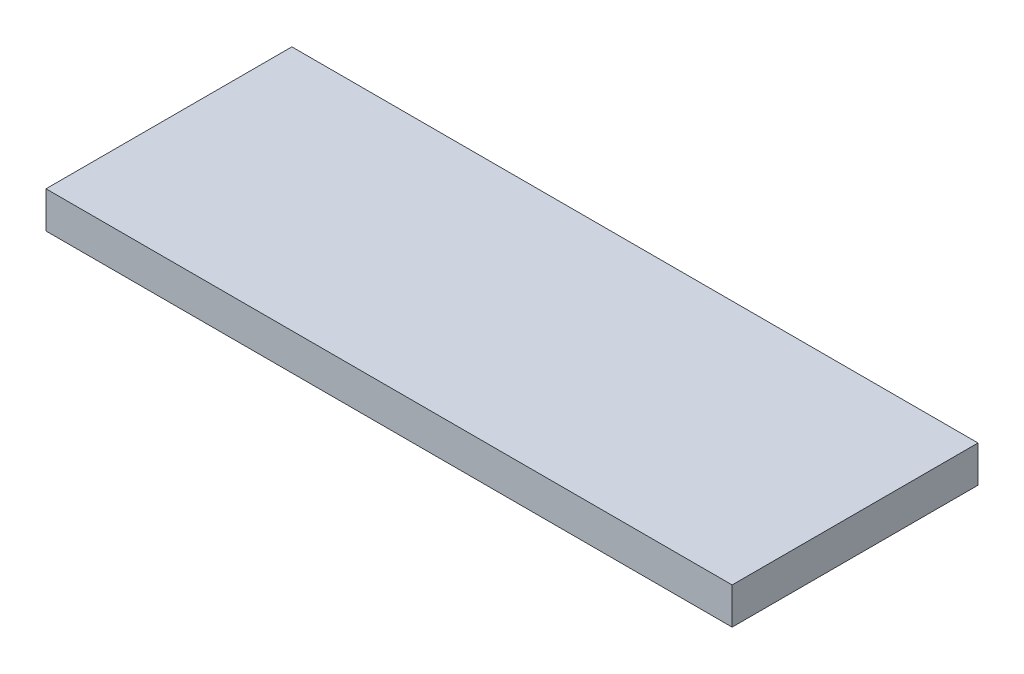
SolidWorks part; units mm, degrees
ref_plane "Front Plane" through (0, 0, 0) normal (0, 0, 1) x (1, 0, 0)
ref_plane "Top Plane" through (0, 0, 0) normal (0, 1, 0) x (1, 0, 0)
ref_plane "Right Plane" through (0, 0, 0) normal (1, 0, 0) x (0, 0, -1)
sketch "Sketch2" plane through (0, 0, 0) normal (0, 1, 0) x (1, 0, 0)
  line L1 (0, 0) -> (30, 0)
  line L2 (0, 0) -> (0, 10.75)
  line L3 (0, 10.75) -> (30, 10.75)
  line L4 (30, 0) -> (30, 10.75)
  dimension "D1" = 30
  dimension "D2" = 10.75
extrude "Boss-Extrude1" add sketch "Sketch2" along normal blind 1.6
equation "\"leftedgewidth\" = 8.5mm"
equation "\"rightedgewidth\" = 10.75mm"
equation "\"innerclipwidth\" = 11.5mm"
equation "\"innerframewidth\" = 99.18mm"
equation "\"framelength\" = 103.2mm"
equation "\"frameextralength\" = 39mm"
equation "\"clipwidth\" = 3mm"
equation "\"cliplength\" = 6mm"
equation "\"clipheight\" = 8mm"
equation "\"basethickness\" = 5mm"
equation "\"framethickness\" = 1.6mm"
equation "\"batterylength\" = 145mm"
equation "\"batterywidth\" = 51mm"
equation "\"D2@Sketch2\"=\"rightedgewidth\""
